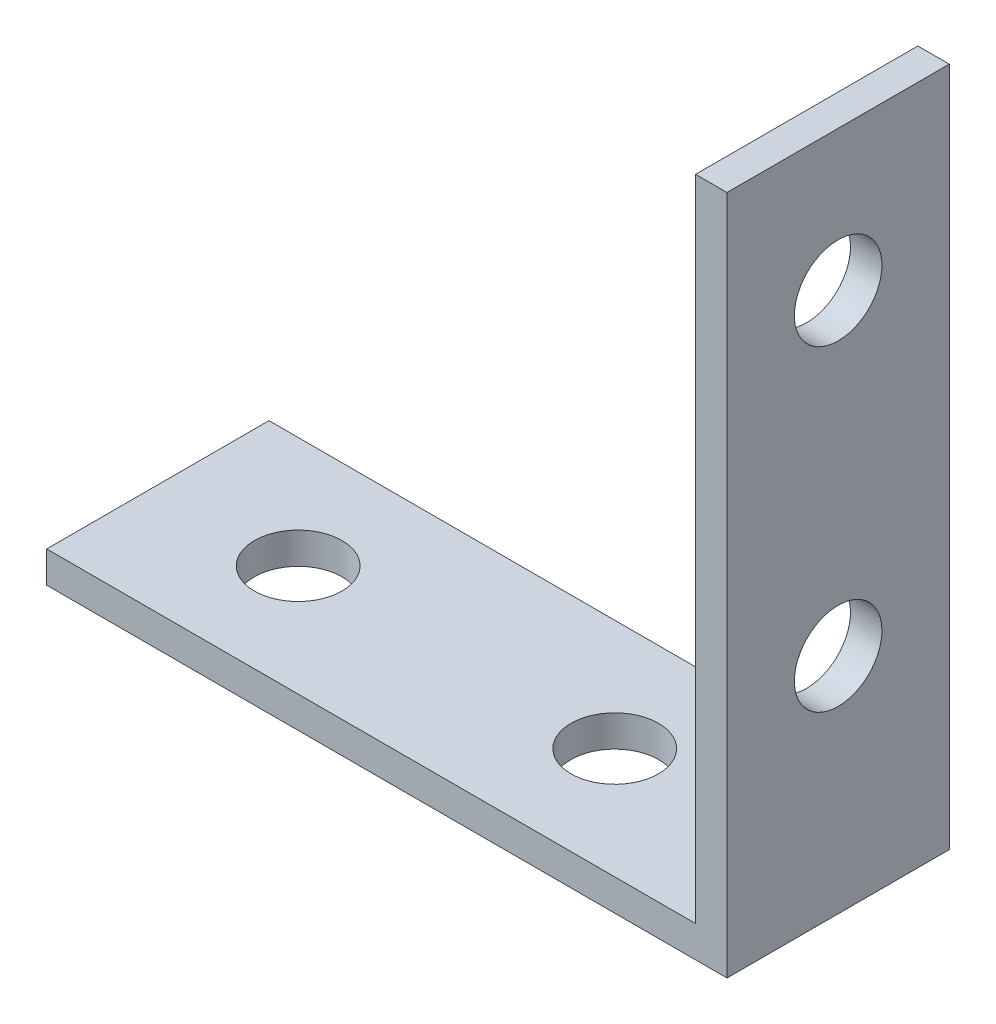
SolidWorks part; units mm, degrees
material "Plain Carbon Steel"
ref_plane "Front Plane" through (0, 0, 0) normal (0, 0, 1) x (1, 0, 0)
ref_plane "Top Plane" through (0, 0, 0) normal (0, 1, 0) x (1, 0, 0)
ref_plane "Right Plane" through (0, 0, 0) normal (1, 0, 0) x (0, 0, -1)
sketch "Sketch1" plane through (0, 0, 0) normal (0, 0, 1) x (1, 0, 0)
  line L1 (0, 0) -> (38.481, 0)
  line L2 (0, 0) -> (0, 38.481)
  line L3 (0, 38.481) -> (38.481, 38.481)
  line L4 (38.481, 0) -> (38.481, 38.481)
  dimension "D1" = 38.481
  dimension "D2" = 38.481
extrude "Boss-Extrude1" add sketch "Sketch1" along normal blind 12.573
sketch "Sketch2" plane through (0, 0, 12.573) normal (0, 0, 1) x (1, 0, 0)
  line L0 (0, 0) -> (38.481, 0) construction
  line L1 (0, 38.481) -> (36.703, 38.481)
  line L2 (0, 38.481) -> (0, 1.778)
  line L3 (0, 1.778) -> (36.703, 1.778)
  line L4 (36.703, 38.481) -> (36.703, 1.778)
  dimension "D1" = 1.778
extrude "Cut-Extrude1" cut sketch "Sketch2" against normal through all
sketch "Sketch3" plane through (36.703, 0, 0) normal (-1, 0, 0) x (0, 0, 1)
  line L0 (6.2865, 38.481) -> (6.2865, 30.5435) construction
  line L1 (0, 38.481) -> (12.573, 38.481) construction
  line L2 (6.2865, 12.6365) -> (6.2865, 0) construction
  line L5 (12.573, 0) -> (0, 0) construction
  circle A0 centre (6.2865, 12.6365) radius 2.4765
  circle A1 centre (6.2865, 30.5435) radius 2.4765
  dimension "D1" = 17.907
  dimension "D2" = 4.953
  dimension "D3" = 12.6365
extrude "Cut-Extrude2" cut sketch "Sketch3" against normal through all
ref_plane "Plane1" through (19.2405, 19.2405, 0) normal (0.7071, 0.7071, 0) x (0, 0, 1)
mirror "Mirror1" about plane through (19.2405, 19.2405, 0) normal (0.7071, 0.7071, 0) of "Cut-Extrude2"
